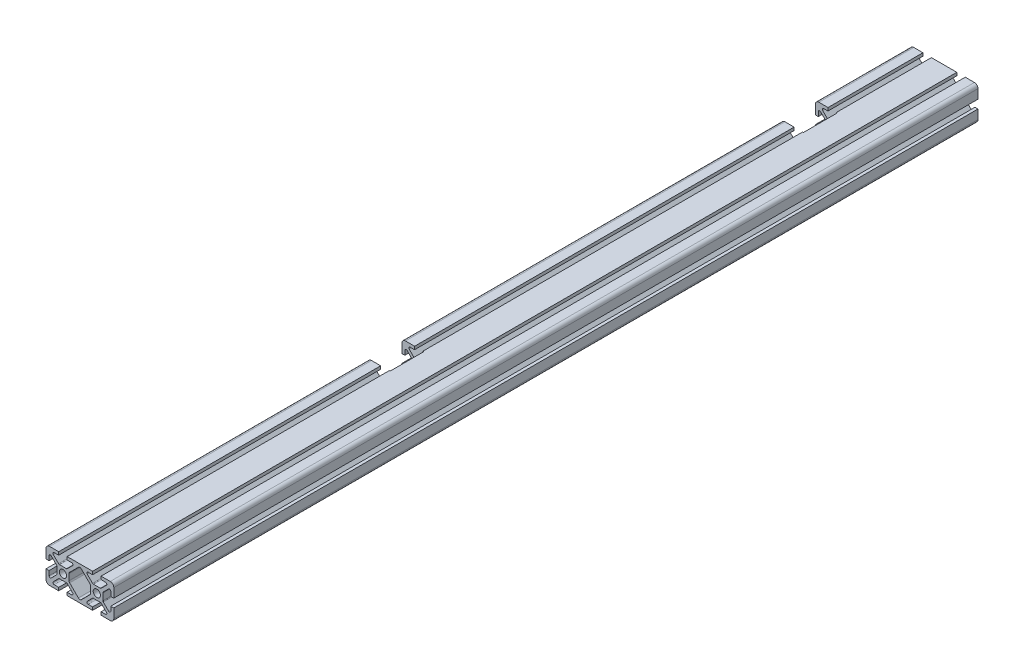
SolidWorks part; units mm, degrees
ref_plane "Front Plane" through (0, 0, 0) normal (0, 0, 1) x (1, 0, 0)
ref_plane "Top Plane" through (0, 0, 0) normal (0, 1, 0) x (1, 0, 0)
ref_plane "Right Plane" through (0, 0, 0) normal (1, 0, 0) x (0, 0, -1)
sketch "Sketch1" plane through (0, 0, 0) normal (0, 0, 1) x (1, 0, 0)
  line L0 (10, 10) -> (10, -10) construction
  line L1 (-20, 0) -> (20, 0) construction
  line L2 (12.5, -10) -> (20, -10)
  line L3 (20, -10) -> (20, -2.5)
  line L4 (12.5, -10) -> (12.5, -8.2134)
  line L5 (12.5, -8.2134) -> (16.95, -8.2134)
  line L6 (16.95, -8.2134) -> (12.3366, -3.6)
  line L7 (10, 0) -> (20, -10) construction
  line L8 (20, -2.5) -> (18.2134, -2.5)
  line L9 (18.2134, -2.5) -> (18.2134, -6.95)
  line L10 (18.2134, -6.95) -> (13.6, -2.3366)
  line L11 (15.9067, -4.6433) -> (14.6433, -5.9067) construction
  line L12 (0, 10) -> (0, -10) construction
  line L13 (0, -10) -> (-20, -10) construction
  line L14 (-10, 10) -> (10, 10) construction
  line L15 (20, 2.5) -> (20, -2.5) construction
  circle A0 centre (10, 0) radius 2.15
  arc A1 (15.5015, -8.2134) -> (15.9257, -7.1891) centre (15.5015, -7.6134) ccw construction
  point P8 (10, -3.6)
  point P16 (15.275, -5.275)
  point P30 (20, 0)
  dimension "Center Hole Diameter" = 4.3
  dimension "D3" = 0.6
  dimension "Rail Width" = 20
  dimension "T-Slot Width" = 5
  dimension "Slot Depth" = 6.4
  dimension "Rail Height" = 40
  dimension "Inner Slot Width" = 13.9
  dimension "Hole Spacing" = 20
sketch "Sketch2" plane through (0, 0, 0) normal (1, 0, 0) x (0, 0, -1)
  line L0 (-1524, -10) -> (1524, -10) construction
  line L1 (-1484, 0) -> (1484, 0) construction
  point P6 (-1484, 0)
  point P8 (1484, 0)
  dimension "Length" = 3048
  dimension "D1" = 40
sketch "Sketch3" plane through (0, 0, 0) normal (0, 0, 1) x (1, 0, 0)
  line L0 (12.5, -10) -> (17.9, -10)
  line L1 (12.5, -10) -> (20, -10) construction
  line L2 (12.5, -10) -> (12.5, -8.2134) construction
  line L3 (12.5, -8.2134) -> (16.95, -8.2134) construction
  line L4 (12.5, -8.2134) -> (12.5, -10)
  line L5 (12.5, -8.2134) -> (16.95, -8.2134)
  line L6 (10, -3.6) -> (12.3366, -3.6)
  line L7 (16.95, -8.2134) -> (12.3366, -3.6) construction
  line L8 (12.3366, -3.6) -> (16.95, -8.2134)
  line L9 (20, -10) -> (20, -2.5) construction
  line L10 (18.2134, -6.95) -> (13.6, -2.3366) construction
  line L11 (18.2134, -2.5) -> (18.2134, -6.95) construction
  line L12 (18.2134, -6.95) -> (18.2134, -2.5)
  line L13 (20, -2.5) -> (18.2134, -2.5) construction
  line L14 (18.2134, -2.5) -> (20, -2.5)
  line L15 (20, -2.5) -> (20, -7.9)
  line L16 (18.2134, -6.95) -> (13.6, -2.3366)
  line L17 (13.6, 0) -> (13.6, -2.3366)
  line L18 (-20, 0) -> (20, 0) construction
  line L19 (10, -3.6) -> (10, -2.15)
  line L20 (10, 10) -> (10, -10) construction
  line L21 (13.6, 0) -> (12.15, 0)
  arc A5 (17.9, -10) -> (20, -7.9) centre (17.9, -7.9) ccw
  circle A10 centre (10, 0) radius 2.15 construction
  arc A11 (10, -2.15) -> (12.15, 0) centre (10, 0) ccw
  dimension "D1" = 2.1
extrude "Boss-Extrude1" add sketch "Sketch3" along normal mid plane 3048
sketch "Sketch4" plane through (0, 0, 0) normal (0, 0, 1) x (1, 0, 0)
  line L0 (10, -3.6) -> (7.6634, -3.6)
  line L4 (7.6634, -3.6) -> (3.05, -8.2134)
  line L5 (3.05, -8.2134) -> (7.5, -8.2134)
  line L6 (7.5, -8.2134) -> (7.5, -10)
  line L18 (7.5, -10) -> (0, -10)
  line L19 (12.5, -10) -> (12.5, -8.2134) construction
  line L20 (12.5, -8.2134) -> (16.95, -8.2134) construction
  line L21 (10, -3.6) -> (12.3366, -3.6) construction
  line L22 (16.95, -8.2134) -> (12.3366, -3.6) construction
  line L23 (0, -8.7366) -> (6.4, -2.3366)
  line L24 (0, 10) -> (0, -10) construction
  line L25 (6.4, -2.3366) -> (6.4, 0)
  line L26 (-20, 0) -> (20, 0) construction
  line L27 (6.4, 0) -> (7.85, 0)
  line L28 (13.6, 0) -> (12.15, 0) construction
  line L29 (0, -8.7366) -> (0, -10)
  line L30 (10, -2.15) -> (10, -3.6)
  circle A4 centre (10, 0) radius 2.15 construction
  arc A5 (7.85, 0) -> (10, -2.15) centre (10, 0) ccw
extrude "Boss-Extrude2" add sketch "Sketch4" along normal mid plane 3048
mirror "Mirror1" about plane through (0, 0, 0) normal (1, 0, 0) of bodies 137 134
mirror "Mirror2" about plane through (0, 0, 0) normal (0, 1, 0) of bodies 135
fillet "Fillet1" radius 0.75 24 edges at (-7.6634, -3.6, 0) (-12.3366, -3.6, 0) (12.3366, -3.6, 0) (7.6634, -3.6, 0) (-3.05, -8.2134, 0) (-18.2134, -6.95, 0) (-16.95, -8.2134, 0) (-13.6, -2.3366, 0) (-18.2134, 6.95, 0) (-16.95, 8.2134, 0) (-12.3366, 3.6, 0) (-7.6634, 3.6, 0) (-13.6, 2.3366, 0) (-3.05, 8.2134, 0) (3.05, 8.2134, 0) (13.6, -2.3366, 0) (18.2134, 6.95, 0) (13.6, 2.3366, 0) (7.6634, 3.6, 0) (12.3366, 3.6, 0) (16.95, 8.2134, 0) (18.2134, -6.95, 0) (16.95, -8.2134, 0) (3.05, -8.2134, 0)
fillet "Fillet2" radius 1.25 6 edges at (0, -8.7366, 0) (-6.4, -2.3366, 0) (0, 8.7366, 0) (-6.4, 2.3366, 0) (6.4, -2.3366, 0) (6.4, 2.3366, 0)
sketch "Sketch5" plane through (-20, 0, 0) normal (-1, 0, 0) x (0, 0, 1)
  line L0 (1524, -10) -> (-1524, -10) construction
  line L1 (1524, 10) -> (-1014, 10)
  line L2 (1524, 10) -> (1524, -10)
  line L3 (1524, -10) -> (-1014, -10)
  line L4 (-1014, 10) -> (-1014, -10)
  line L5 (-1524, 7.9) -> (-1524, 2.5) construction
  dimension "D1" = 510
extrude "Cut-Extrude1" cut sketch "Sketch5" against normal through all
sketch "Sketch6" plane through (0, 10, 0) normal (0, 1, 0) x (1, 0, 0)
  line L0 (-20, 1014) -> (-20, 1524) construction
  line L1 (-20, 1224) -> (-7, 1224)
  line L2 (-20, 1224) -> (-20, 1204)
  line L3 (-20, 1204) -> (-7, 1204)
  line L4 (-7, 1224) -> (-7, 1204)
  line L5 (-7.5, 1524) -> (7.5, 1524) construction
  line L6 (-20, 1524) -> (-20, 1463) construction
  line L8 (-20, 1468) -> (-7, 1468)
  line L9 (-20, 1468) -> (-20, 1448)
  line L10 (-20, 1448) -> (-7, 1448)
  line L11 (-7, 1468) -> (-7, 1448)
  dimension "D1" = 320
  dimension "D2" = 20
  dimension "D3" = 13
  dimension "D4" = 61
  dimension "D5" = 13
  dimension "D6" = 20
  dimension "D7" = 5
extrude "Cut-Extrude2" cut sketch "Sketch6" against normal blind 40
equation "\"D1@Sketch3\" = \"D3@Sketch1\" * 3.5"
equation "\"D1@Boss-Extrude1\" = \"Length@Sketch2\""
equation "\"D1@Boss-Extrude2\" = \"Length@Sketch2\""
equation "\"D1@Sketch2\"=\"Rail Height@Sketch1\""
